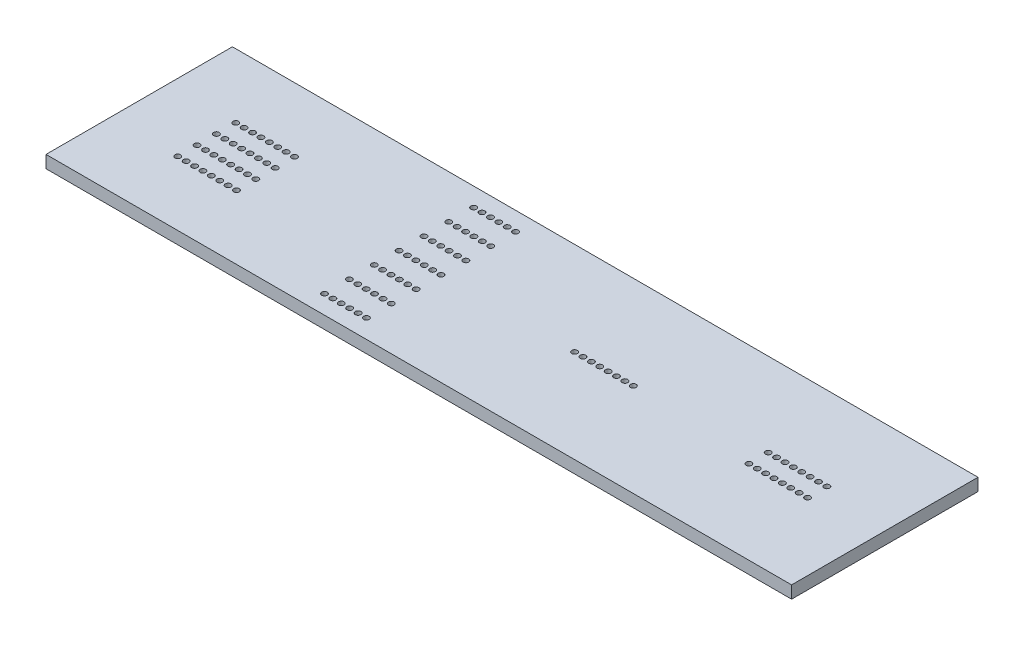
SolidWorks part; units mm, degrees
ref_plane "Plan de face" through (0, 0, 0) normal (0, 0, 1) x (1, 0, 0)
ref_plane "Plan de dessus" through (0, 0, 0) normal (0, 1, 0) x (1, 0, 0)
ref_plane "Plan de droite" through (0, 0, 0) normal (1, 0, 0) x (0, 0, -1)
sketch "Esquisse2" plane through (0, 0, 0) normal (0, 1, 0) x (1, 0, 0)
  line L1 (-60, -15) -> (60, -15)
  line L2 (-60, -15) -> (-60, 15)
  line L3 (-60, 15) -> (60, 15)
  line L4 (60, -15) -> (60, 15)
  line L5 (-60, -15) -> (60, 15) construction
  line L6 (-60, 15) -> (60, -15) construction
  point P0 (0, 0)
  dimension "D1" = 30
  dimension "D2" = 120
extrude "Boss.-Extru.1" add sketch "Esquisse2" along normal blind 2 contours L3 L4 L1 L2
sketch "Cavités" plane through (0, 0, 0) normal (0, 1, 0) x (1, 0, 0)
  line L0 (-60, -15) -> (60, -15) construction
  line L1 (-58.4, 15) -> (-30.4, 15) construction
  line L2 (-58.4, 15) -> (-58.4, -15) construction
  line L3 (-58.4, -15) -> (-30.4, -15) construction
  line L4 (-30.4, 15) -> (-30.4, -15) construction
  line L5 (-60, 15) -> (60, 15) construction
  line L6 (-28.8, 15) -> (-0.8, 15) construction
  line L7 (-28.8, 15) -> (-28.8, -15) construction
  line L8 (-28.8, -15) -> (-0.8, -15) construction
  line L9 (-0.8, 15) -> (-0.8, -15) construction
  line L10 (-30.4, 15) -> (-28.8, 15) construction
  line L11 (0.8, 15) -> (28.8, 15) construction
  line L12 (0.8, 15) -> (0.8, -15) construction
  line L13 (0.8, -15) -> (28.8, -15) construction
  line L14 (28.8, 15) -> (28.8, -15) construction
  line L15 (30.4, 15) -> (58.4, 15) construction
  line L16 (30.4, 15) -> (30.4, -15) construction
  line L17 (30.4, -15) -> (58.4, -15) construction
  line L18 (58.4, 15) -> (58.4, -15) construction
  line L19 (-0.8, 15) -> (0.8, 15) construction
  line L20 (28.8, 15) -> (30.4, 15) construction
  line L21 (-60, 15) -> (-58.4, 15) construction
  line L22 (58.4, 15) -> (60, 15) construction
  dimension "D1" = 28
  dimension "D2" = 1.6
sketch "Esquisse7" plane through (0, 2, 0) normal (0, 1, 0) x (1, 0, 0)
  line L0 (-58.4, 0) -> (-49.125, 0) construction
  line L1 (-49.125, 4.6665) -> (-39.675, 4.6665) construction
  line L2 (-49.125, 4.6665) -> (-49.125, -4.6665) construction
  line L3 (-49.125, -4.6665) -> (-39.675, -4.6665) construction
  line L4 (-39.675, 4.6665) -> (-39.675, -4.6665) construction
  line L5 (-58.4, 15) -> (-58.4, -15) construction
  line L6 (-39.675, 0) -> (-30.4, 0) construction
  line L7 (-30.4, 15) -> (-30.4, -15) construction
  dimension "D1" = 9.45
  dimension "D2" = 9.333
sketch "Esquisse8" plane through (0, 2, 0) normal (0, 1, 0) x (1, 0, 0)
  circle A0 centre (-49.125, 4.6665) radius 0.45
  dimension "D1" = 0.9
extrude "Enlèv. mat.-Extru.3" cut sketch "Esquisse8" against normal up to next
pattern_linear "Répétition linéaire4" count 8 spacing 1.35 along (1, 0, 0) count 4 spacing 3.111 along (0, 0, 1) of "Enlèv. mat.-Extru.3"
sketch "Esquisse9" plane through (0, 2, 0) normal (0, 1, 0) x (1, 0, 0)
  line L0 (-28.8, 0) -> (-18.175, 0) construction
  line L1 (-18.175, 12) -> (-11.425, 12) construction
  line L2 (-18.175, 12) -> (-18.175, -12) construction
  line L3 (-18.175, -12) -> (-11.425, -12) construction
  line L4 (-11.425, 12) -> (-11.425, -12) construction
  line L5 (-28.8, 15) -> (-28.8, -15) construction
  line L6 (-11.425, 0) -> (-0.8, 0) construction
  line L7 (-0.8, 15) -> (-0.8, -15) construction
  dimension "D1" = 6.75
  dimension "D2" = 24
sketch "Esquisse10" plane through (0, 2, 0) normal (0, 1, 0) x (1, 0, 0)
  circle A0 centre (-18.175, 12) radius 0.45
  dimension "D1" = 0.9
extrude "Enlèv. mat.-Extru.4" cut sketch "Esquisse10" against normal up to next
pattern_linear "Répétition linéaire5" count 6 spacing 1.35 along (1, 0, 0) count 7 spacing 4 along (0, 0, 1) of "Enlèv. mat.-Extru.4"
sketch "Esquisse11" plane through (0, 2, 0) normal (0, 1, 0) x (1, 0, 0)
  line L0 (0.8, 0) -> (10.075, 0) construction
  line L5 (0.8, 15) -> (0.8, -15) construction
  line L6 (19.525, 0) -> (28.8, 0) construction
  line L7 (28.8, 15) -> (28.8, -15) construction
  line L8 (10.075, 0) -> (19.525, 0) construction
  dimension "D1" = 9.45
sketch "Esquisse12" plane through (0, 2, 0) normal (0, 1, 0) x (1, 0, 0)
  circle A0 centre (10.075, 0) radius 0.45
  dimension "D1" = 0.9
extrude "Enlèv. mat.-Extru.5" cut sketch "Esquisse12" against normal up to next
pattern_linear "Répétition linéaire6" count 8 spacing 1.35 along (1, 0, 0) of "Enlèv. mat.-Extru.5"
sketch "Esquisse13" plane through (0, 2, 0) normal (0, 1, 0) x (1, 0, 0)
  line L0 (30.4, 0) -> (39.675, 0) construction
  line L1 (39.675, 1.555) -> (49.125, 1.555) construction
  line L2 (39.675, 1.555) -> (39.675, -1.555) construction
  line L3 (39.675, -1.555) -> (49.125, -1.555) construction
  line L4 (49.125, 1.555) -> (49.125, -1.555) construction
  line L5 (30.4, 15) -> (30.4, -15) construction
  line L6 (49.125, 0) -> (58.4, 0) construction
  line L7 (58.4, 15) -> (58.4, -15) construction
  dimension "D1" = 3.11
  dimension "D2" = 9.45
sketch "Esquisse14" plane through (0, 2, 0) normal (0, 1, 0) x (1, 0, 0)
  circle A0 centre (39.675, 1.555) radius 0.45
  dimension "D1" = 0.9
extrude "Enlèv. mat.-Extru.6" cut sketch "Esquisse14" against normal up to next
pattern_linear "Répétition linéaire7" count 8 spacing 1.35 along (1, 0, 0) count 2 spacing 3.11 along (0, 0, 1) of "Enlèv. mat.-Extru.6"
